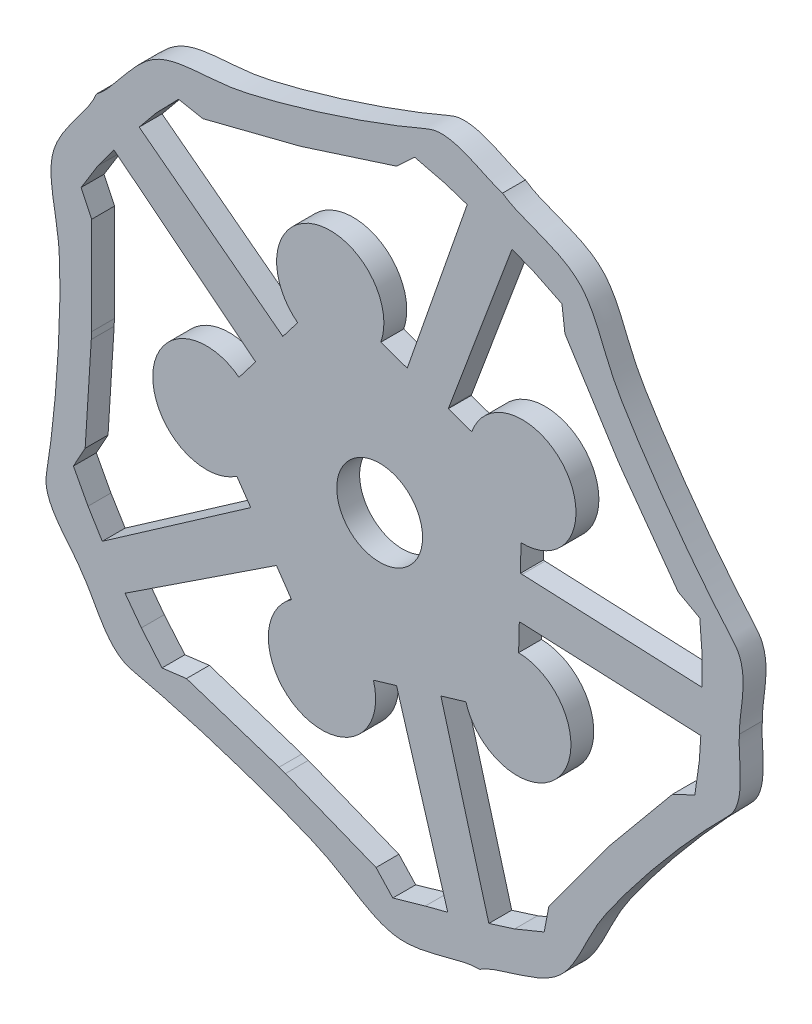
SolidWorks part; units mm, degrees
ref_plane "Front Plane" through (0, 0, 0) normal (0, 0, 1) x (1, 0, 0)
ref_plane "Top Plane" through (0, 0, 0) normal (0, 1, 0) x (1, 0, 0)
ref_plane "Right Plane" through (0, 0, 0) normal (1, 0, 0) x (0, 0, -1)
sketch "Sketch1" plane through (0, 0, 0) normal (0, 0, 1) x (1, 0, 0)
  line L0 (-1533.7906, -661.1296) -> (-467.1239, -661.1296) construction
  line L1 (-7.5152, 5.8865) -> (-19.8034, 15.4534) construction
  line L2 (-14.2276, -7.8289) -> (-13.3862, -9.0707) construction
  line L3 (4.2802, -8.9548) -> (6.0276, -8.4351)
  line L4 (-7.5152, -6.9985) -> (-6.4698, -8.585) construction
  line L5 (-9.0626, -4.2307) -> (-9.0135, -4.1968)
  line L6 (-7.2884, -6.849) -> (-7.2191, -6.8013)
  line L7 (9.8666, -1.7174) -> (9.7635, -1.7174)
  line L8 (9.9573, 1.2467) -> (9.8378, 1.2467)
  line L9 (4.8361, 8.7946) -> (4.8031, 8.7011)
  line L10 (1.9677, 9.8331) -> (1.9264, 9.7161)
  line L11 (-6.7985, 7.313) -> (-6.7666, 7.2886)
  line L12 (22.535, 0.6972) -> (9.9573, 1.2467)
  line L13 (-8.7223, 4.8419) -> (-8.6702, 4.802)
  line L14 (3.1929, -22.2182) -> (3.842, -24.7969) construction
  line L15 (7.004, -24.1444) -> (0.8358, -2.8812) construction
  line L16 (-20.163, 0.4088) -> (-20.1476, 0.8851)
  line L17 (22.5516, 2.5881) -> (22.535, 0.6972)
  line L18 (22.3825, 4.8146) -> (22.5516, 2.5881)
  line L19 (20.872, 5.6441) -> (22.3825, 4.8146)
  line L20 (16.8748, 11.1635) -> (20.872, 5.6441)
  line L21 (3.2761, 8.9664) -> (8.5914, 23.6479) construction
  line L22 (-16.8129, 14.9428) -> (-6.7985, 7.313)
  line L23 (-15.6151, 16.406) -> (-16.8129, 14.9428)
  line L24 (16.6072, 11.5578) -> (16.8748, 11.1635)
  line L25 (16.6072, 11.5578) -> (12.9557, 17.3118)
  line L26 (12.9557, 17.3118) -> (12.743, 19.0219)
  line L27 (12.743, 19.0219) -> (10.7366, 20.0018)
  line L28 (10.7366, 20.0018) -> (9.2531, 20.5838)
  line L29 (9.2531, 20.5838) -> (4.8361, 8.7946)
  line L30 (-0.4377, -10.3581) -> (1.1806, -9.8767)
  line L31 (-14.0599, 18.0082) -> (-15.6151, 16.406)
  line L32 (-12.3685, 17.6785) -> (-14.0599, 18.0082)
  line L33 (-5.3063, 19.4914) -> (-5.7643, 19.3598)
  line L34 (-5.7643, 19.3598) -> (-12.3685, 17.6785)
  line L35 (-5.3063, 19.4914) -> (1.1825, 21.5742)
  line L36 (1.1825, 21.5742) -> (2.4406, 22.7518)
  line L37 (4.6093, 22.2201) -> (6.1215, 21.7176)
  line L38 (2.4406, 22.7518) -> (4.6093, 22.2201)
  line L39 (6.1215, 21.7176) -> (1.9677, 9.8331)
  line L40 (-20.1373, 7.6999) -> (-20.8717, 9.2588)
  line L41 (-18.5749, 12.6795) -> (-8.7223, 4.8419)
  line L42 (-19.6998, 11.1595) -> (-18.5749, 12.6795)
  line L43 (-20.8717, 9.2588) -> (-19.6998, 11.1595)
  line L44 (-20.1476, 0.8851) -> (-20.1373, 7.6999)
  line L45 (-20.163, 0.4088) -> (-20.5909, -6.3926)
  line L46 (-20.5909, -6.3926) -> (-21.4116, -7.8787)
  line L47 (-13.6486, 8.7607) -> (-12.7272, 9.9443) construction
  line L48 (-11.8057, 11.1279) -> (-12.7272, 9.9443) construction
  line L49 (-21.4116, -7.8787) -> (-20.3889, -9.8006)
  line L50 (-0.2549, -21.6092) -> (0.9198, -22.8701)
  line L51 (0.9198, -22.8701) -> (3.1929, -22.2182)
  line L52 (3.1929, -22.2182) -> (4.7613, -21.814)
  line L53 (4.7613, -21.814) -> (1.1806, -9.8767)
  line L54 (-7.0339, -18.9248) -> (-6.586, -19.0875)
  line L55 (-6.586, -19.0875) -> (-0.2549, -21.6092)
  line L56 (-7.0339, -18.9248) -> (-13.5076, -16.7958)
  line L57 (-16.6596, -15.3041) -> (-17.8012, -13.7759)
  line L58 (-15.2177, -17.009) -> (-16.6596, -15.3041)
  line L59 (-13.5076, -16.7958) -> (-15.2177, -17.009)
  line L60 (-17.8012, -13.7759) -> (-7.2884, -6.849)
  line L61 (16.1321, -12.0585) -> (15.8397, -12.4348)
  line L62 (22.4536, -2.2647) -> (9.8666, -1.7174)
  line L63 (22.3486, -3.8659) -> (22.4536, -2.2647)
  line L64 (22.0367, -6.0769) -> (22.3486, -3.8659)
  line L65 (20.476, -6.8076) -> (22.0367, -6.0769)
  line L66 (16.1321, -12.0585) -> (20.476, -6.8076)
  line L67 (15.8397, -12.4348) -> (11.8257, -17.942)
  line L68 (11.8257, -17.942) -> (11.5035, -19.6349)
  line L69 (11.5035, -19.6349) -> (9.4382, -20.4837)
  line L70 (9.4382, -20.4837) -> (7.6348, -21.0523)
  line L71 (7.6348, -21.0523) -> (4.2802, -8.9548)
  line L72 (2.9527, -15.7846) -> (4.4527, -15.3495) construction
  line L73 (5.9527, -14.9863) -> (4.4527, -15.3495) construction
  line L74 (-20.7844, -14.0838) -> (-2.4835, -1.6829) construction
  line L75 (-12.5448, -10.3125) -> (-13.3862, -9.0707) construction
  line L76 (-20.3889, -9.8006) -> (-19.3927, -11.4272)
  line L77 (-7.7187, 6.045) -> (-7.7843, 5.9592)
  line L78 (-19.3927, -11.4272) -> (-9.0626, -4.2307)
  line L79 (4.0446, 15.7754) -> (5.5446, 15.2323) construction
  line L80 (7.0446, 14.6892) -> (5.5446, 15.2323) construction
  line L81 (25.1593, -0.8249) -> (3, 0) construction
  line L82 (9.7159, -3.6171) -> (9.7635, -1.7174)
  line L83 (16.1601, -1.9911) -> (16.1917, -0.4911) construction
  line L84 (6.4425, 8.1226) -> (4.8031, 8.7011)
  line L85 (-5.7342, 8.6372) -> (-6.7666, 7.2886)
  line L86 (-9.9864, -2.7845) -> (-9.0135, -4.1968)
  line L87 (-8.6702, 4.802) -> (-9.8344, 3.2812)
  line L88 (-8.116, -5.4995) -> (-8.073, -5.5618)
  line L89 (-7.2191, -6.8013) -> (-6.1596, -8.3391)
  line L90 (9.8002, -0.2531) -> (9.8004, -0.2456)
  line L91 (9.8378, 1.2467) -> (9.8849, 3.126)
  line L93 (1.9264, 9.7161) -> (0.0816, 10.367)
  circle A0 centre (0, 0) radius 3
  circle A1 centre (0, 0) radius 9.8035 construction
  arc A3 (-6.1596, -8.3391) -> (-0.4377, -10.3581) centre (-4.0321, -11.4272) ccw
  arc A8 (-9.8344, 3.2812) -> (-9.9864, -2.7845) centre (-12.1139, 0.3036) ccw
  arc A9 (6.0276, -8.4351) -> (9.7159, -3.6171) centre (9.6219, -7.366) ccw
  arc A10 (9.8849, 3.126) -> (6.2853, 7.5235) centre (9.9788, 6.8748) ccw
  arc A11 (0.0816, 10.367) -> (-5.7342, 8.6372) centre (-3.4547, 11.6148) ccw
  spline S0 degree 3 poles (-19.8034, 15.4534) (-18.4059, 16.4806) (-16.8657, 19.7328) (-13.0801, 20.3515) (-10.5527, 20.4539) (-7.1088, 21.2649) (-2.6538, 22.5809) (1.4711, 24.0955) (5.0388, 25.6709) (7.3241, 23.9986) (8.5914, 23.6479) knots 0 0 0 0 0.190522 0.271148 0.35187 0.432694 0.60507 0.80034 0.829758 1 1 1 1
  spline S1 degree 3 poles (-19.8034, 15.4534) (-20.4565, 13.8468) (-23.2317, 11.556) (-22.9031, 7.7343) (-22.3826, 5.259) (-22.3244, 1.7213) (-22.5077, -2.9203) (-22.9644, -7.2908) (-23.6168, -11.1358) (-21.4351, -12.9413) (-20.7844, -14.0838) knots 0 0 0 0 0.190522 0.271148 0.35187 0.432694 0.60507 0.80034 0.829758 1 1 1 1
  spline S2 degree 3 poles (7.004, -24.1444) (5.2698, -24.154) (2.112, -25.8797) (-1.3142, -24.1552) (-3.4191, -22.7525) (-6.682, -21.3843) (-11.0597, -19.8305) (-15.2871, -18.6311) (-19.0994, -17.8086) (-19.9653, -15.1124) (-20.7844, -14.0838) knots 0 0 0 0 0.190522 0.271148 0.35187 0.432694 0.60507 0.80034 0.829758 1 1 1 1
  spline S3 degree 3 poles (7.004, -24.1444) (8.4768, -23.2285) (12.0684, -23.0064) (14.049, -19.7215) (15.0828, -17.413) (17.1151, -14.5167) (19.9917, -10.8693) (22.9301, -7.602) (25.718, -4.8747) (25.0142, -2.1318) (25.1593, -0.8249) knots 0 0 0 0 0.190522 0.271148 0.35187 0.432694 0.60507 0.80034 0.829758 1 1 1 1
  spline S4 degree 3 poles (8.5914, 23.6479) (10.0001, 22.6363) (13.5691, 22.1764) (15.3273, 18.7673) (16.2057, 16.3952) (18.0413, 13.3705) (20.6696, 9.5403) (23.3847, 6.0852) (25.9855, 3.179) (25.1012, 0.4887) (25.1593, -0.8249) knots 0 0 0 0 0.190522 0.271148 0.35187 0.432694 0.60507 0.80034 0.829758 1 1 1 1
extrude "Boss-Extrude1" add sketch "Sketch1" along normal blind 1.6
